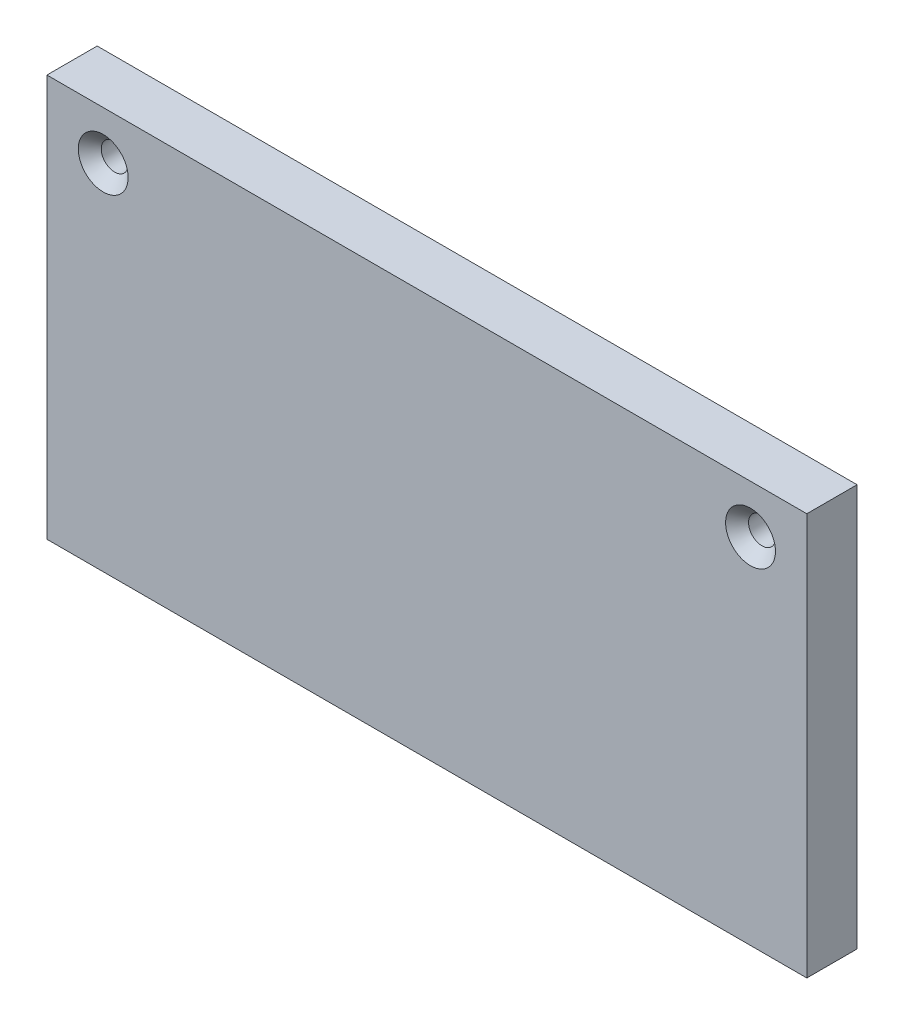
SolidWorks part; units mm, degrees
ref_plane "Front Plane" through (0, 0, 0) normal (0, 0, 1) x (1, 0, 0)
ref_plane "Top Plane" through (0, 0, 0) normal (0, 1, 0) x (1, 0, 0)
ref_plane "Right Plane" through (0, 0, 0) normal (1, 0, 0) x (0, 0, -1)
sketch "Sketch1" plane through (0, 0, 0) normal (0, 0, 1) x (1, 0, 0)
  line L0 (0, 0) -> (96.012, 0)
  line L1 (96.012, 0) -> (96.012, 50.8)
  line L2 (96.012, 50.8) -> (0, 50.8)
  line L3 (0, 50.8) -> (0, 0)
  dimension "D1" = 96.012
  dimension "D2" = 50.8
extrude "Boss-Extrude1" add sketch "Sketch1" along normal blind 6.35
sketch "Sketch2" plane through (0, 0, 6.35) normal (0, 0, 1) x (1, 0, 0)
  line L4 (96.012, 50.8) -> (0, 50.8) construction
  line L5 (0, 50.8) -> (0, 0) construction
  line L6 (96.012, 0) -> (96.012, 50.8) construction
  circle A0 centre (7.112, 44.704) radius 1.4986
  circle A1 centre (88.9, 44.704) radius 1.4986
  point P11 (0, 0)
  dimension "D1" = 6.096
  dimension "D3" = 2.9972
  dimension "D5" = 2.9972
  dimension "D2" = 7.112
  dimension "D4" = 7.112
  dimension "D6" = 6.096
hole_wizard "CSK for M3 Flat Head Machine Screw2" positions "Sketch5" profile "Sketch6" countersink size "M3" standard "ANSI Metric" end condition through all
sketch "Sketch5" plane through (0, 0, 6.35) normal (0, 0, 1) x (1, 0, 0)
  point P0 (7.112, 44.704)
  point P3 (88.9, 44.704)
sketch "Sketch6" plane through (7.112, 44.704, 6.35) normal (1, 0, 0) x (0, -1, 0)
  line L0 (0, 0) -> (0, 6.35)
  line L1 (0, 6.35) -> (1.7, 6.35)
  line L2 (1.7, 6.35) -> (1.7, 1.45)
  line L3 (1.7, 1.45) -> (3.15, 0)
  line L5 (3.15, 0) -> (0, 0)
  line L6 (-1.7, 1.45) -> (-3.15, 0) construction
  line L11 (0, -6.35) -> (0, 107.95) construction
  dimension "Thru Hole Dia." = 3.4
  dimension "Thru Hole Depth" = 6.35
  dimension "Near C'Sink Dia." = 6.3
  dimension "Near C'Sink Angle" = 90
sketch "Sketch7" plane through (0, 0, 6.35) normal (0, 0, 1) x (1, 0, 0)
  text T0 "KIRILL NEKRYUKOV"
